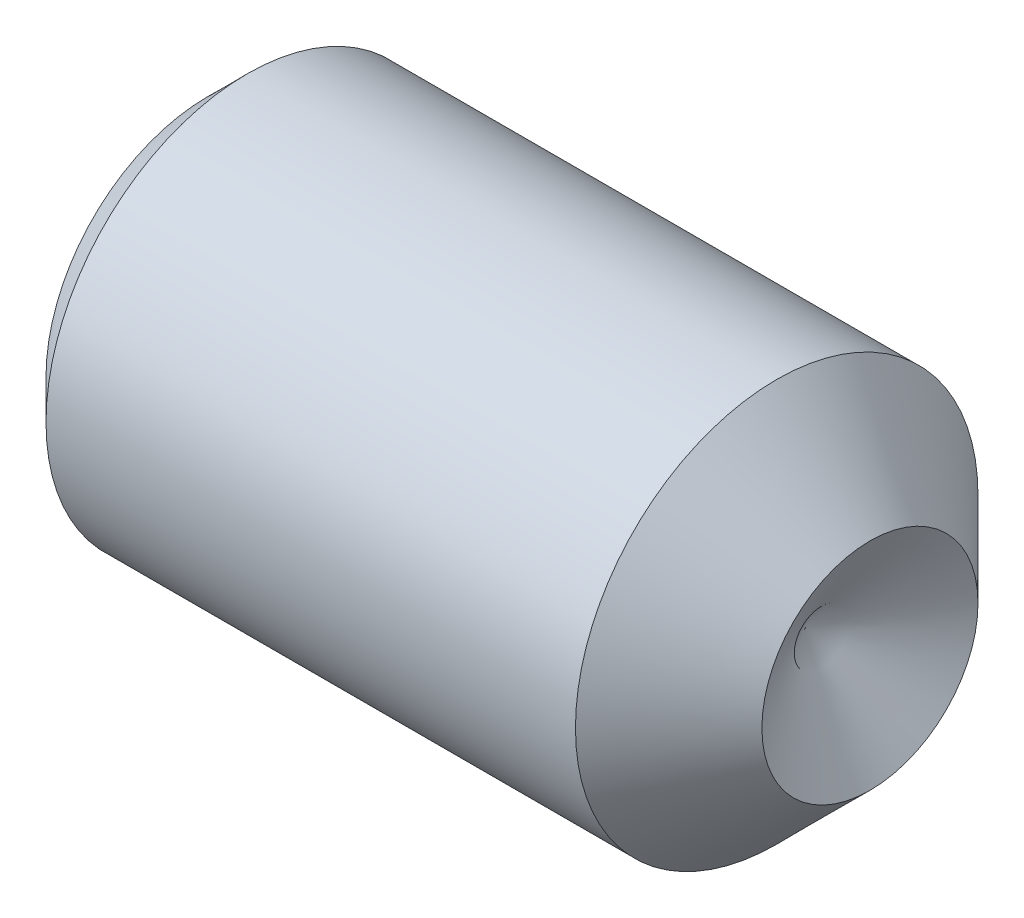
SolidWorks part; units mm, degrees
material "Alloy Steel"
ref_plane "Plane1" through (0, 0, 0) normal (0, 0, 1) x (1, 0, 0)
ref_plane "Plane2" through (0, 0, 0) normal (0, 1, 0) x (1, 0, 0)
ref_plane "Plane3" through (0, 0, 0) normal (1, 0, 0) x (0, 0, -1)
revolve "BaseBody" add sketch "BodySke" angle 360 about L5
sketch "BodySke" plane through (0, 0, 0) normal (0, 0, 1) x (1, 0, 0)
  line L0 (0, 0) -> (0, 1.9406)
  line L1 (0, 1.9406) -> (0.4724, 2.413)
  line L2 (0.4724, 2.413) -> (6.8199, 2.413)
  line L3 (6.8199, 2.413) -> (7.9375, 1.2954)
  line L4 (7.1591, 0) -> (0, 0)
  line L5 (-12.7, 0) -> (88.9, 0) construction
  line L6 (7.1591, 0) -> (7.9375, 1.2954)
  line L7 (7.9375, 1.2954) -> (7.9375, 10.8204) construction
  line L8 (0, -1.9406) -> (0.4724, -2.413) construction
  line L9 (7.1591, 0) -> (7.9375, -1.2954) construction
  line L10 (6.8199, -2.413) -> (7.9375, -1.2954) construction
  line L11 (0.7925, 15.875) -> (0.7925, -3.175) construction
  dimension "Length" = 7.9375
  dimension "Diameter" = 4.826
  dimension "Drive_ch_ang" = 45
  dimension "Minor_dia" = 3.8811
  dimension "Cup_nose_ang" = 45
  dimension "Cup_ang" = 118
  dimension "Cup_dia" = 2.5908
  dimension "Advance" = 0.7925
cosmetic thread "ThreadCosmetic" parameters "Thread_minor"=3.8811
sketch "Sketch2" plane through (0, 0, 0) normal (-1, 0, 0) x (0, 0, 1)
  line L0 (0.687, 1.19) -> (-0.687, 1.19)
  line L1 (-0.687, 1.19) -> (-1.3741, 0)
  line L2 (0.687, 1.19) -> (1.3741, 0)
  line L3 (0.687, -1.19) -> (1.3741, 0)
  line L4 (0.687, -1.19) -> (-0.687, -1.19)
  line L5 (-0.687, -1.19) -> (-1.3741, 0)
  dimension "Hex_size" = 2.38
  dimension "D2" = 1.19
  dimension "D3" = 1.19
extrude "Hex" cut sketch "Sketch2" against normal blind 2.54
sketch "Sketch4" plane through (0, 4.7709, -0.5249) normal (-1, 0, 0) x (0, 0, 1)
  line L0 (0.5249, -4.7709) -> (1.9854, -4.7709)
  line L1 (0.5249, -4.7709) -> (6.6732, -1.2211) construction
  line L2 (0.5249, -4.7709) -> (1.2551, -3.506)
  line L3 (1.7258, -4.4441) -> (1.9182, -4.333)
  line L4 (1.4083, -3.8942) -> (1.6007, -3.7831)
  arc A0 (1.7258, -4.4441) -> (1.4083, -3.8942) centre (0.5249, -4.7709) ccw
  arc A1 (1.9854, -4.7709) -> (1.9182, -4.333) centre (0.5249, -4.7709) ccw
  arc A2 (1.2551, -3.506) -> (1.6007, -3.7831) centre (0.5249, -4.7709) cw
  circle A3 centre (0.5249, -4.7709) radius 1.2446 construction
  circle A4 centre (0.5249, -4.7709) radius 1.4605 construction
  dimension "D1" = 30
  dimension "Spline_n_dim" = 2.4892
  dimension "Spline_m_dim" = 2.921
  dimension "Spline_a_dim" = 60
  dimension "D3" = 0.3175
  dimension "Spline_p_dim" = 0.635
extrude "Spline" [suppressed] cut sketch "Sketch4" against normal blind 2.032
pattern_circular "CirPattern1" [suppressed] count 6 every 60 about axis through (-12.7, 0, 0) along (1, 0, 0)
sketch "ThdSchSke" plane through (0, 0, 0) normal (0, 0, 1) x (1, 0, 0)
  line L0 (0.4724, -1.9406) -> (0.1416, -2.413)
  line L1 (0.4724, -1.9406) -> (0.8032, -2.413)
  line L2 (0.8032, -2.413) -> (0.8032, -3.0162)
  line L3 (-3.175, 0) -> (5.1513, 0) construction
  line L4 (0.4724, 2.413) -> (0.4724, -2.413) construction
  line L5 (0.8032, -3.0162) -> (0.1416, -3.0162)
  line L6 (0.1416, -3.0162) -> (0.1416, -2.413)
  dimension "Thread_minor" = 3.8811
  dimension "Diameter" = 4.826
  dimension "SideAngle" = 55
  dimension "VeeAngle" = 70
  dimension "Overcut" = 6.0325
revolve "ThreadSchematic" [suppressed] cut sketch "ThdSchSke" angle 360 about L3
pattern_linear "ThdSchPat" [suppressed]
equation "\"D2@Sketch2\" = \"Hex_size@Sketch2\" / 2"
equation "\"D3@Sketch2\" = \"Hex_size@Sketch2\" / 2"
equation "\"Thread_minor@ThreadCosmetic\" = \"Minor_dia@BodySke\""
equation "\"D1@Sketch4\" = \"Spline_a_dim@Sketch4\" / 2"
equation "\"D3@Sketch4\" = \"Spline_p_dim@Sketch4\" / 2"
equation "\"D2@CirPattern1\" = \"Spline_a_dim@Sketch4\""
equation "\"Num_teeth@CirPattern1\" = 360 / \"D2@CirPattern1\""
equation "\"Thread_minor@ThdSchSke\" = \"Thread_minor@ThreadCosmetic\""
equation "\"Diameter@ThdSchSke\" = \"Diameter@BodySke\""
equation "\"Overcut@ThdSchSke\" = \"Diameter@BodySke\" * 1.25"
equation "\"Num_threads@ThdSchPat\" = int( (\"Length@BodySke\" - ( ( ( \"Diameter@BodySke\" - \"Minor_dia@BodySke\" ) * 0.5 ) / tan( \"Drive_ch_ang@BodySke\" * 0.017453292 ) ) - ( ( ( \"Diameter@BodySke\" - \"Cup_dia@BodySke\" ) * 0.5 ) * tan( \"Cup_nose_ang@BodySke\" * 0.017453292 ) ) ) / \"Advance@BodySke\" + 0.999 )  + 1"
equation "\"Advance@ThdSchPat\" = (\"Length@BodySke\" - ( ( ( \"Diameter@BodySke\" - \"Minor_dia@BodySke\" ) * 0.5 ) / tan( \"Drive_ch_ang@BodySke\" * 0.017453292 ) ) - ( ( ( \"Diameter@BodySke\" - \"Cup_dia@BodySke\" ) * 0.5 ) * tan( \"Cup_nose_ang@BodySke\" * 0.017453292 ) ) ) /  (\"Num_threads@ThdSchPat\" - 1) 'relax it"
equation "' \"Num_threads@ThdSchPat\" = \"Num_threads@ThdSchPat\" - sgn( \"Num_threads@ThdSchPat\" - 1) '---chamfered tips only---"
